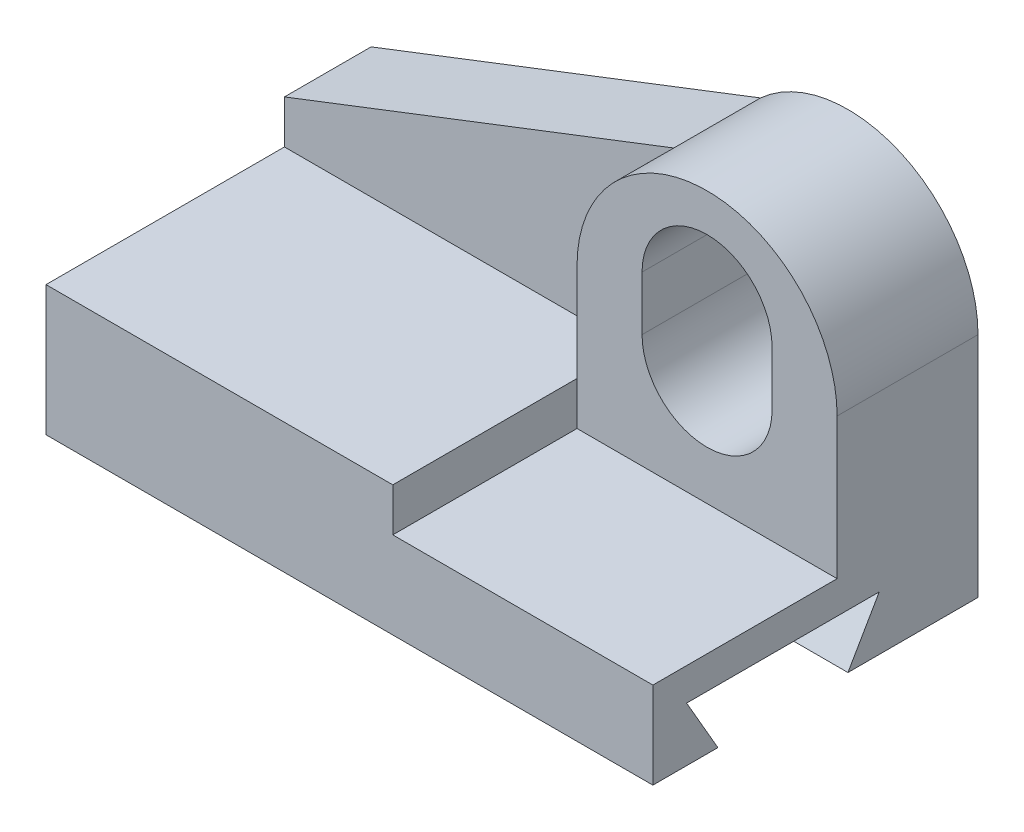
SolidWorks part; units mm, degrees
ref_plane "前视基准面" through (0, 0, 0) normal (0, 0, 1) x (1, 0, 0)
ref_plane "上视基准面" through (0, 0, 0) normal (0, 1, 0) x (1, 0, 0)
ref_plane "右视基准面" through (0, 0, 0) normal (1, 0, 0) x (0, 0, -1)
other "Configuration Table"
sketch "草图1" plane through (0, 0, 0) normal (0, 1, 0) x (1, 0, 0)
  line L1 (-28, -15) -> (28, -15)
  line L2 (-28, -15) -> (-28, 15)
  line L3 (-28, 15) -> (28, 15)
  line L4 (28, -15) -> (28, 15)
  line L5 (-28, -15) -> (28, 15) construction
  line L6 (-28, 15) -> (28, -15) construction
  point P0 (0, 0)
  dimension "D1" = 30
  dimension "D2" = 56
extrude "凸台-拉伸1" add sketch "草图1" along normal blind 8
sketch "草图2" plane through (0, 8, 0) normal (0, 1, 0) x (1, 0, 0)
  line L1 (-28, -15) -> (4, -15)
  line L2 (-28, -15) -> (-28, 7)
  line L3 (-28, 7) -> (4, 7)
  line L4 (4, -15) -> (4, 7)
  dimension "D1" = 32
  dimension "D2" = 22
extrude "凸台-拉伸2" add sketch "草图2" along normal blind 4
sketch "草图3" plane through (-28, 0, 0) normal (-1, 0, 0) x (0, 0, 1)
  line L0 (15, 0) -> (9, 0)
  line L1 (-15, 0) -> (15, 0) construction
  line L2 (9, 0) -> (11.8868, 5)
  line L3 (9, 0) -> (-3, 0)
  line L4 (-3, 0) -> (-5.8868, 5)
  line L5 (-5.8868, 5) -> (11.8868, 5)
  line L6 (9, 0) -> (-3, 0)
  dimension "D1" = 6
  dimension "D2" = 60
  dimension "D3" = 5
  dimension "D4" = 12
  dimension "D5" = 60
  dimension "D6" = 5
extrude "切除-拉伸1" cut sketch "草图3" against normal through all contours L3 L4 L5 L2
sketch "草图4" plane through (0, 8, 0) normal (0, 1, 0) x (1, 0, 0)
  line L1 (-28, 15) -> (4, 15)
  line L2 (-28, 15) -> (-28, 7)
  line L3 (-28, 7) -> (4, 7)
  line L4 (4, 15) -> (4, 7)
extrude "凸台-拉伸3" add sketch "草图4" along normal blind 8
ref_plane "基准面1" through (0, 0, -15) normal (0, 0, -1) x (-1, 0, 0)
sketch "草图7" plane through (0, 0, -15) normal (0, 0, -1) x (-1, 0, 0)
  line L0 (-28, 8) -> (-28, 21)
  line L1 (-4, 8) -> (-4, 21)
  line L3 (-16, 21) -> (-10, 21)
  line L4 (-16, 21) -> (-22, 21)
  line L5 (-22, 21) -> (-22, 16)
  line L6 (-10, 21) -> (-10, 16)
  line L7 (-10, 16) -> (-22, 16)
  line L8 (-28, 8) -> (-4, 8)
  arc A0 (-4, 21) -> (-28, 21) centre (-16, 21) ccw
  arc A1 (-10, 21) -> (-22, 21) centre (-16, 21) ccw
  arc A2 (-10, 16) -> (-22, 16) centre (-16, 16) cw
  dimension "D1" = 13
  dimension "D2" = 13
  dimension "D3" = 6
  dimension "D4" = 6
  dimension "D5" = 5
extrude "凸台-拉伸8" add sketch "草图7" against normal blind 13 contours A0 L0 L8 L1
sketch "草图8" plane through (0, 0, -15) normal (0, 0, -1) x (-1, 0, 0)
  line L9 (-22, 18.5) -> (-22, 23.5)
  line L10 (-10, 23.5) -> (-10, 18.5)
  arc A3 (-22, 23.5) -> (-10, 23.5) centre (-16, 23.5) cw
  arc A4 (-22, 18.5) -> (-10, 18.5) centre (-16, 18.5) ccw
  point P11 (-16, 18.5)
extrude "切除-拉伸2" cut sketch "草图8" against normal through all
ref_plane "基准面2" through (0, 0, -11) normal (0, 0, 1) x (1, 0, 0)
sketch "草图13" plane through (0, 0, -11) normal (0, 0, 1) x (1, 0, 0)
  line L0 (-28, 16) -> (16, 33)
  dimension "D1" = 17
  dimension "D2" = 44
rib "筋1" sketch "草图13" sketch "草图13" thickness 8 extrusion direction parallel to sketch draft on no parameters "D1"=8
